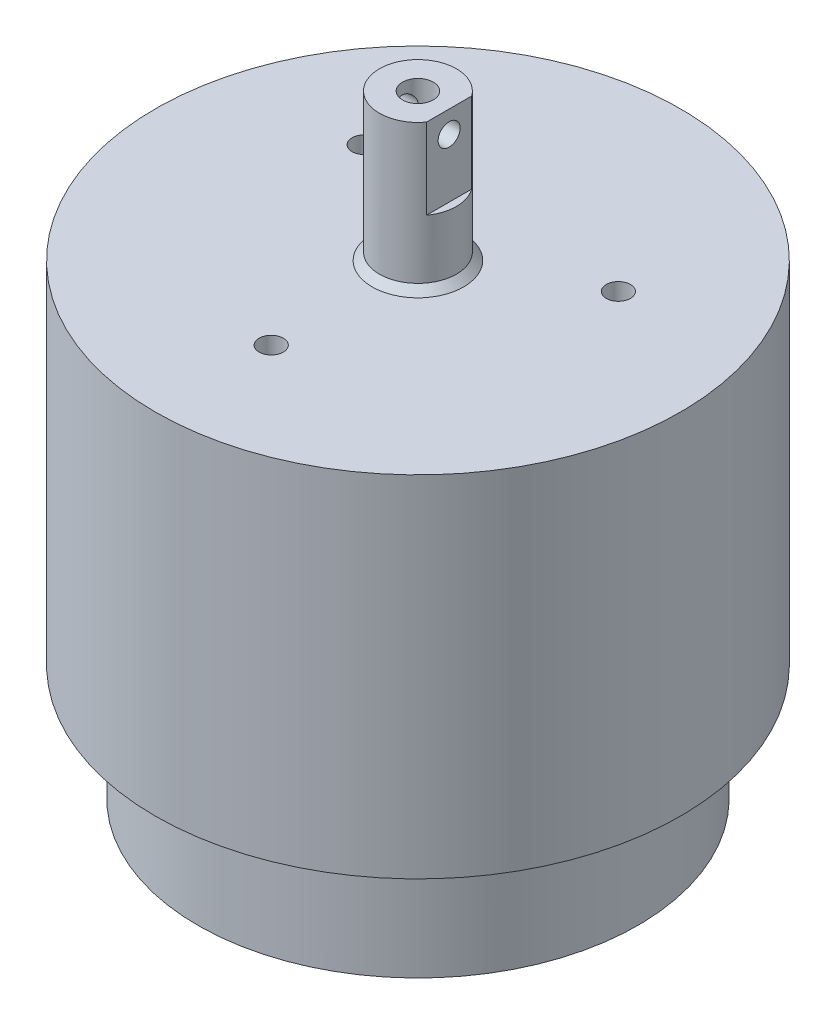
SolidWorks part; units mm, degrees
ref_plane "前视基准面" through (0, 0, 0) normal (0, 0, 1) x (1, 0, 0)
ref_plane "上视基准面" through (0, 0, 0) normal (0, 1, 0) x (1, 0, 0)
ref_plane "右视基准面" through (0, 0, 0) normal (1, 0, 0) x (0, 0, -1)
sketch "草图1" plane through (0, 0, 0) normal (0, 1, 0) x (1, 0, 0)
  circle A0 centre (0, 0) radius 35.8
  dimension "D1" = 71.6
extrude "凸台-拉伸1" add sketch "草图1" along normal blind 47.7
sketch "草图2" plane through (0, 47.7, 0) normal (0, 1, 0) x (1, 0, 0)
  circle A0 centre (0, 0) radius 5.25
  dimension "D1" = 10.5
extrude "凸台-拉伸2" add sketch "草图2" along normal blind 20
sketch "草图3" plane through (0, 67.7, 0) normal (0, 1, 0) x (1, 0, 0)
  line L1 (4.25, 3.0822) -> (11.3888, 3.0822)
  line L2 (4.25, 3.0822) -> (4.25, -3.0822)
  line L3 (4.25, -3.0822) -> (11.3888, -3.0822)
  line L4 (11.3888, 3.0822) -> (11.3888, -3.0822)
  circle A0 centre (0, 0) radius 5.25 construction
  dimension "D1" = 4.25
extrude "切除-拉伸1" cut sketch "草图3" against normal blind 11
sketch "草图4" plane through (4.25, 0, 0) normal (1, 0, 0) x (0, 0, -1)
  line L0 (3.0822, 67.7) -> (-3.0822, 67.7) construction
  circle A0 centre (0, 64.7) radius 1.5
  dimension "D1" = 3
  dimension "D2" = 3
extrude "切除-拉伸2" cut sketch "草图4" against normal through all
chamfer "倒角1" distance 1 angle 45 1 edges at (0, 47.7, 5.25)
sketch "草图5" plane through (0, 47.7, 0) normal (0, 1, 0) x (1, 0, 0)
  circle A0 centre (0, -20) radius 1.65
  circle A1 centre (0, 0) radius 20
  circle A2 centre (-17.3205, 10) radius 1.65
  circle A3 centre (17.3205, 10) radius 1.65
  point P11 (0, 0)
  dimension "D1" = 3.3
  dimension "D2" = 40
  dimension "D3" = 0
  dimension "D4" = 3
extrude "切除-拉伸3" cut sketch "草图5" against normal blind 6 contours A1 A3 | A1 A3 | A0 A1 | A1 A0 | A1 A2 | A1 A2
cosmetic thread "装饰螺纹线1" parameters "D2"=4
cosmetic thread "装饰螺纹线2" parameters "D2"=4
cosmetic thread "装饰螺纹线3" parameters "D2"=4
sketch "草图6" plane through (0, 67.7, 0) normal (0, 1, 0) x (1, 0, 0)
  circle A0 centre (0, 0) radius 2.1
  dimension "D1" = 4.2
extrude "切除-拉伸4" cut sketch "草图6" against normal blind 24
cosmetic thread "装饰螺纹线4" parameters "D1"=10, "D2"=5
sketch "草图7" plane through (0, 0, 0) normal (0, -1, 0) x (1, 0, 0)
  circle A0 centre (0, 0) radius 30
  dimension "D1" = 60
extrude "凸台-拉伸3" add sketch "草图7" along normal blind 15.8
sketch "草图8" plane through (0, 0, 0) normal (1, 0, 0) x (0, 0, -1)
  line L0 (-30, 0) -> (-30, -15.8) construction
  line L1 (30, 0) -> (26.8, 0)
  line L2 (30, 0) -> (30, -12)
  line L3 (30, -12) -> (26.8, -12)
  line L4 (26.8, 0) -> (26.8, -12)
  line L5 (-30, -15.8) -> (30, -15.8) construction
  dimension "D1" = 56.8
  dimension "D2" = 3.8
extrude "切除-拉伸5" cut sketch "草图8" against normal mid plane 136.8
